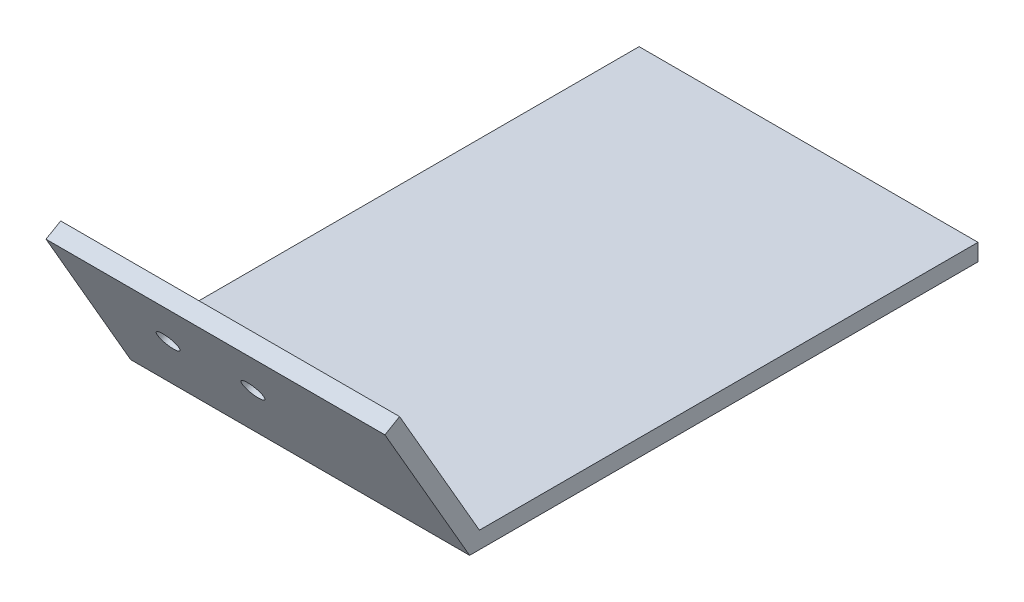
SolidWorks part; units mm, degrees
ref_plane "Front Plane" through (0, 0, 0) normal (0, 0, 1) x (1, 0, 0)
ref_plane "Top Plane" through (0, 0, 0) normal (0, 1, 0) x (1, 0, 0)
ref_plane "Right Plane" through (0, 0, 0) normal (1, 0, 0) x (0, 0, -1)
sketch "Sketch1" plane through (0, 0, 0) normal (1, 0, 0) x (0, 0, -1)
  line L0 (0, 0) -> (-25, 43.3013)
  line L1 (-25, 43.3013) -> (-20.6699, 45.8013)
  line L2 (-20.6699, 45.8013) -> (2.8868, 5)
  line L3 (2.8868, 5) -> (150, 5)
  line L4 (150, 5) -> (150, 0)
  line L5 (150, 0) -> (0, 0)
  dimension "D1" = 120
  dimension "D2" = 50
  dimension "D3" = 5
  dimension "D4" = 150
extrude "Boss-Extrude1" add sketch "Sketch1" along normal blind 100
sketch "Sketch2" plane through (0, 2.5, -4.3301) normal (0, 0.5, -0.866) x (-1, 0, 0)
  line L0 (-100, 2.8868) -> (0, 2.8868) construction
  line L1 (-100, 2.8868) -> (-100, 50) construction
  circle A0 centre (-50, 27.8868) radius 3.175
  circle A1 centre (-25, 27.8868) radius 3.175
  dimension "D3" = 6.35
  dimension "D1" = 25
  dimension "D2" = 25
  dimension "D4" = 50
extrude "Cut-Extrude1" cut sketch "Sketch2" against normal through all
